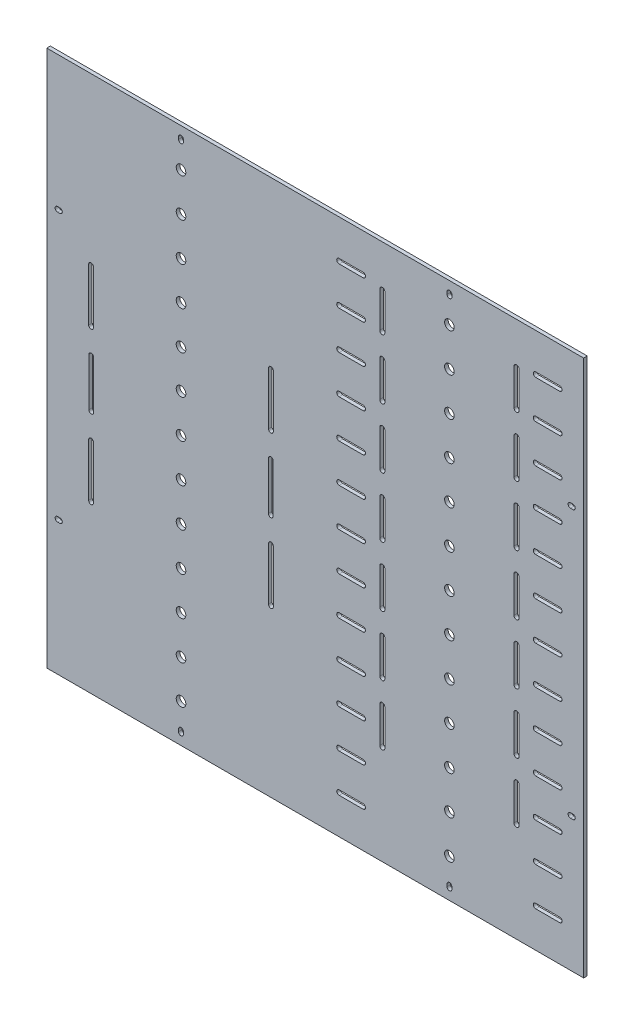
SolidWorks part; units mm, degrees
ref_plane "Piano frontale" through (0, 0, 0) normal (0, 0, 1) x (1, 0, 0)
ref_plane "Piano superiore" through (0, 0, 0) normal (0, 1, 0) x (1, 0, 0)
ref_plane "Piano destro" through (0, 0, 0) normal (1, 0, 0) x (0, 0, -1)
sketch "Schizzo1" plane through (0, 0, 0) normal (0, 0, 1) x (1, 0, 0)
  line L0 (10, 448) -> (10, -28.2593) construction
  line L1 (0, 0) -> (448, 0)
  line L2 (0, 0) -> (0, 448)
  line L3 (0, 448) -> (448, 448)
  line L4 (448, 0) -> (448, 448)
  line L5 (0, 224) -> (448, 224) construction
  line L6 (224, 448) -> (224, 0) construction
  line L7 (438, 448) -> (438, -28.2593) construction
  line L8 (0, 438) -> (525.0128, 438) construction
  line L9 (0, 10) -> (525.0128, 10) construction
  line L10 (0, 448) -> (0, 224) construction
  line L11 (0, 448) -> (0, 224) construction
  line L12 (9, 336) -> (11, 336) construction
  line L13 (9, 338) -> (11, 338)
  line L14 (9, 334) -> (11, 334)
  line L15 (0, 336) -> (224, 336) construction
  line L16 (9, 112) -> (11, 112) construction
  line L17 (9, 110) -> (11, 110)
  line L18 (9, 114) -> (11, 114)
  line L19 (439, 112) -> (437, 112) construction
  line L20 (439, 110) -> (437, 110)
  line L21 (439, 114) -> (437, 114)
  line L22 (439, 336) -> (437, 336) construction
  line L23 (439, 338) -> (437, 338)
  line L24 (439, 334) -> (437, 334)
  line L25 (112, 448) -> (112, 224) construction
  line L26 (112, 439) -> (112, 437) construction
  line L27 (114, 439) -> (114, 437)
  line L28 (110, 439) -> (110, 437)
  line L29 (336, 439) -> (336, 437) construction
  line L30 (334, 439) -> (334, 437)
  line L31 (338, 439) -> (338, 437)
  line L32 (112, 9) -> (112, 11) construction
  line L33 (114, 9) -> (114, 11)
  line L34 (110, 9) -> (110, 11)
  line L35 (336, 9) -> (336, 11) construction
  line L36 (334, 9) -> (334, 11)
  line L37 (338, 9) -> (338, 11)
  line L38 (36.9588, 287.1268) -> (36.9588, 448) construction
  line L39 (36.9588, 265.3661) -> (36.9588, 309.3661) construction
  line L40 (34.9588, 265.3661) -> (34.9588, 309.3661)
  line L41 (38.9588, 265.3661) -> (38.9588, 309.3661)
  line L42 (36.9588, 182.6339) -> (36.9588, 138.6339) construction
  line L43 (34.9588, 182.6339) -> (34.9588, 138.6339)
  line L44 (38.9588, 182.6339) -> (38.9588, 138.6339)
  line L45 (37.087, 204.1388) -> (37.087, 244.1388) construction
  line L46 (35.087, 204.1388) -> (35.087, 244.1388)
  line L47 (39.087, 204.1388) -> (39.087, 244.1388)
  line L48 (187.0412, 265.3661) -> (187.0412, 309.3661) construction
  line L49 (189.0412, 265.3661) -> (189.0412, 309.3661)
  line L50 (185.0412, 265.3661) -> (185.0412, 309.3661)
  line L51 (186.913, 204.1388) -> (186.913, 244.1388) construction
  line L52 (188.913, 204.1388) -> (188.913, 244.1388)
  line L53 (184.913, 204.1388) -> (184.913, 244.1388)
  line L54 (187.0412, 182.6339) -> (187.0412, 138.6339) construction
  line L55 (189.0412, 182.6339) -> (189.0412, 138.6339)
  line L56 (185.0412, 182.6339) -> (185.0412, 138.6339)
  line L57 (243.9707, 416) -> (263.9707, 416) construction
  line L58 (243.9707, 418) -> (263.9707, 418)
  line L59 (243.9707, 414) -> (263.9707, 414)
  line L63 (224, 224) -> (448, 0) construction
  line L64 (448, 224) -> (224, 0) construction
  line L65 (224, 224) -> (448, 224) construction
  line L66 (336, 112) -> (335.9892, 224.0001) construction
  line L67 (336, 112) -> (448, 112) construction
  line L83 (427.9707, 416.0177) -> (407.9707, 416.0139) construction
  line L84 (427.9703, 418.0177) -> (407.9703, 418.0139)
  line L85 (427.9711, 414.0177) -> (407.9711, 414.0139)
  line L89 (243.9707, 384) -> (263.9707, 384) construction
  line L90 (243.9707, 386) -> (263.9707, 386)
  line L91 (243.9707, 382) -> (263.9707, 382)
  line L92 (427.9707, 384.0177) -> (407.9707, 384.0139) construction
  line L93 (427.9703, 386.0177) -> (407.9703, 386.0139)
  line L94 (427.9711, 382.0177) -> (407.9711, 382.0139)
  line L95 (279.9725, 383.005) -> (279.9725, 412.995) construction
  line L96 (277.8725, 383.005) -> (277.8725, 412.995)
  line L97 (282.0725, 383.005) -> (282.0725, 412.995)
  line L98 (243.9707, 352) -> (263.9707, 352) construction
  line L99 (243.9707, 354) -> (263.9707, 354)
  line L100 (243.9707, 350) -> (263.9707, 350)
  line L101 (427.9707, 352.0177) -> (407.9707, 352.0139) construction
  line L102 (427.9703, 354.0177) -> (407.9703, 354.0139)
  line L103 (427.9711, 350.0177) -> (407.9711, 350.0139)
  line L104 (243.9707, 320) -> (263.9707, 320) construction
  line L105 (243.9707, 322) -> (263.9707, 322)
  line L106 (243.9707, 318) -> (263.9707, 318)
  line L107 (427.9707, 320.0177) -> (407.9707, 320.0139) construction
  line L108 (427.9703, 322.0177) -> (407.9703, 322.0139)
  line L109 (427.9711, 318.0177) -> (407.9711, 318.0139)
  line L110 (243.9707, 288) -> (263.9707, 288) construction
  line L111 (391.9724, 383.0058) -> (391.9724, 413.0158) construction
  line L112 (394.0724, 383.0058) -> (394.0724, 413.0158)
  line L113 (389.8724, 383.0058) -> (389.8724, 413.0158)
  line L114 (336, 112) -> (202.345, 112) construction
  line L118 (243.9707, 290) -> (263.9707, 290)
  line L122 (243.9707, 286) -> (263.9707, 286)
  line L132 (427.9707, 288.0177) -> (407.9707, 288.0139) construction
  line L133 (427.9703, 290.0177) -> (407.9703, 290.0139)
  line L134 (427.9711, 286.0177) -> (407.9711, 286.0139)
  line L135 (243.9707, 256) -> (263.9707, 256) construction
  line L136 (243.9707, 258) -> (263.9707, 258)
  line L137 (243.9707, 254) -> (263.9707, 254)
  line L138 (427.9707, 256.0177) -> (407.9707, 256.0139) construction
  line L139 (427.9703, 258.0177) -> (407.9703, 258.0139)
  line L140 (427.9711, 254.0177) -> (407.9711, 254.0139)
  line L141 (243.9707, 224) -> (263.9707, 224) construction
  line L142 (243.9707, 226) -> (263.9707, 226)
  line L143 (243.9707, 222) -> (263.9707, 222)
  line L144 (427.9707, 224.0177) -> (407.9707, 224.0139) construction
  line L145 (427.9703, 226.0177) -> (407.9703, 226.0139)
  line L146 (427.9711, 222.0177) -> (407.9711, 222.0139)
  line L147 (243.9707, 192) -> (263.9707, 192) construction
  line L148 (243.9707, 194) -> (263.9707, 194)
  line L149 (243.9707, 190) -> (263.9707, 190)
  line L150 (427.9707, 192.0177) -> (407.9707, 192.0139) construction
  line L151 (427.9703, 194.0177) -> (407.9703, 194.0139)
  line L152 (427.9711, 190.0177) -> (407.9711, 190.0139)
  line L153 (243.9707, 160) -> (263.9707, 160) construction
  line L154 (243.9707, 162) -> (263.9707, 162)
  line L155 (243.9707, 158) -> (263.9707, 158)
  line L156 (427.9707, 160.0177) -> (407.9707, 160.0139) construction
  line L157 (427.9703, 162.0177) -> (407.9703, 162.0139)
  line L158 (427.9711, 158.0177) -> (407.9711, 158.0139)
  line L159 (243.9707, 128) -> (263.9707, 128) construction
  line L160 (243.9707, 130) -> (263.9707, 130)
  line L161 (243.9707, 126) -> (263.9707, 126)
  line L162 (427.9707, 128.0177) -> (407.9707, 128.0139) construction
  line L163 (427.9703, 130.0177) -> (407.9703, 130.0139)
  line L164 (427.9711, 126.0177) -> (407.9711, 126.0139)
  line L165 (279.9725, 333.005) -> (279.9725, 362.995) construction
  line L166 (277.8725, 333.005) -> (277.8725, 362.995)
  line L167 (282.0725, 333.005) -> (282.0725, 362.995)
  line L168 (391.9724, 333.0058) -> (391.9724, 363.0158) construction
  line L169 (394.0724, 333.0058) -> (394.0724, 363.0158)
  line L170 (389.8724, 333.0058) -> (389.8724, 363.0158)
  line L171 (279.9725, 283.005) -> (279.9725, 312.995) construction
  line L172 (277.8725, 283.005) -> (277.8725, 312.995)
  line L173 (282.0725, 283.005) -> (282.0725, 312.995)
  line L174 (391.9724, 283.0058) -> (391.9724, 313.0158) construction
  line L175 (394.0724, 283.0058) -> (394.0724, 313.0158)
  line L176 (389.8724, 283.0058) -> (389.8724, 313.0158)
  line L177 (279.9725, 233.005) -> (279.9725, 262.995) construction
  line L178 (277.8725, 233.005) -> (277.8725, 262.995)
  line L179 (282.0725, 233.005) -> (282.0725, 262.995)
  line L180 (391.9724, 233.0058) -> (391.9724, 263.0158) construction
  line L181 (394.0724, 233.0058) -> (394.0724, 263.0158)
  line L182 (389.8724, 233.0058) -> (389.8724, 263.0158)
  line L183 (279.9725, 183.005) -> (279.9725, 212.995) construction
  line L184 (277.8725, 183.005) -> (277.8725, 212.995)
  line L185 (282.0725, 183.005) -> (282.0725, 212.995)
  line L186 (391.9724, 183.0058) -> (391.9724, 213.0158) construction
  line L187 (394.0724, 183.0058) -> (394.0724, 213.0158)
  line L188 (389.8724, 183.0058) -> (389.8724, 213.0158)
  line L189 (279.9725, 133.005) -> (279.9725, 162.995) construction
  line L190 (277.8725, 133.005) -> (277.8725, 162.995)
  line L191 (282.0725, 133.005) -> (282.0725, 162.995)
  line L192 (391.9724, 133.0058) -> (391.9724, 163.0158) construction
  line L193 (394.0724, 133.0058) -> (394.0724, 163.0158)
  line L194 (389.8724, 133.0058) -> (389.8724, 163.0158)
  line L195 (279.9725, 83.005) -> (279.9725, 112.995) construction
  line L196 (277.8725, 83.005) -> (277.8725, 112.995)
  line L197 (282.0725, 83.005) -> (282.0725, 112.995)
  line L198 (391.9724, 83.0058) -> (391.9724, 113.0158) construction
  line L199 (394.0724, 83.0058) -> (394.0724, 113.0158)
  line L200 (389.8724, 83.0058) -> (389.8724, 113.0158)
  line L201 (243.9707, 96) -> (263.9707, 96) construction
  line L202 (243.9707, 98) -> (263.9707, 98)
  line L203 (243.9707, 94) -> (263.9707, 94)
  line L204 (427.9707, 96.0177) -> (407.9707, 96.0139) construction
  line L205 (427.9703, 98.0177) -> (407.9703, 98.0139)
  line L206 (427.9711, 94.0177) -> (407.9711, 94.0139)
  line L207 (243.9707, 64) -> (263.9707, 64) construction
  line L208 (243.9707, 66) -> (263.9707, 66)
  line L209 (243.9707, 62) -> (263.9707, 62)
  line L210 (427.9707, 64.0177) -> (407.9707, 64.0139) construction
  line L211 (427.9703, 66.0177) -> (407.9703, 66.0139)
  line L212 (427.9711, 62.0177) -> (407.9711, 62.0139)
  line L213 (243.9707, 32) -> (263.9707, 32) construction
  line L214 (243.9707, 34) -> (263.9707, 34)
  line L215 (243.9707, 30) -> (263.9707, 30)
  line L216 (427.9707, 32.0177) -> (407.9707, 32.0139) construction
  line L217 (427.9703, 34.0177) -> (407.9703, 34.0139)
  line L218 (427.9711, 30.0177) -> (407.9711, 30.0139)
  arc A0 (9, 338) -> (9, 334) centre (9, 336) ccw
  arc A1 (11, 334) -> (11, 338) centre (11, 336) ccw
  arc A2 (9, 110) -> (9, 114) centre (9, 112) cw
  arc A3 (11, 114) -> (11, 110) centre (11, 112) cw
  arc A4 (439, 110) -> (439, 114) centre (439, 112) ccw
  arc A5 (437, 114) -> (437, 110) centre (437, 112) ccw
  arc A6 (439, 338) -> (439, 334) centre (439, 336) cw
  arc A7 (437, 334) -> (437, 338) centre (437, 336) cw
  arc A8 (114, 439) -> (110, 439) centre (112, 439) ccw
  arc A9 (110, 437) -> (114, 437) centre (112, 437) ccw
  arc A10 (334, 439) -> (338, 439) centre (336, 439) cw
  arc A11 (338, 437) -> (334, 437) centre (336, 437) cw
  arc A12 (114, 9) -> (110, 9) centre (112, 9) cw
  arc A13 (110, 11) -> (114, 11) centre (112, 11) cw
  arc A14 (334, 9) -> (338, 9) centre (336, 9) ccw
  arc A15 (338, 11) -> (334, 11) centre (336, 11) ccw
  arc A16 (34.9588, 265.3661) -> (38.9588, 265.3661) centre (36.9588, 265.3661) ccw
  arc A17 (38.9588, 309.3661) -> (34.9588, 309.3661) centre (36.9588, 309.3661) ccw
  arc A18 (34.9588, 182.6339) -> (38.9588, 182.6339) centre (36.9588, 182.6339) cw
  arc A19 (38.9588, 138.6339) -> (34.9588, 138.6339) centre (36.9588, 138.6339) cw
  arc A20 (35.087, 204.1388) -> (39.087, 204.1388) centre (37.087, 204.1388) ccw
  arc A21 (39.087, 244.1388) -> (35.087, 244.1388) centre (37.087, 244.1388) ccw
  arc A22 (189.0412, 265.3661) -> (185.0412, 265.3661) centre (187.0412, 265.3661) cw
  arc A23 (185.0412, 309.3661) -> (189.0412, 309.3661) centre (187.0412, 309.3661) cw
  arc A24 (188.913, 204.1388) -> (184.913, 204.1388) centre (186.913, 204.1388) cw
  arc A25 (184.913, 244.1388) -> (188.913, 244.1388) centre (186.913, 244.1388) cw
  arc A26 (189.0412, 182.6339) -> (185.0412, 182.6339) centre (187.0412, 182.6339) ccw
  arc A27 (185.0412, 138.6339) -> (189.0412, 138.6339) centre (187.0412, 138.6339) ccw
  arc A28 (243.9707, 418) -> (243.9707, 414) centre (243.9707, 416) ccw
  arc A29 (263.9707, 414) -> (263.9707, 418) centre (263.9707, 416) ccw
  arc A36 (427.9703, 418.0177) -> (427.9711, 414.0177) centre (427.9707, 416.0177) cw
  arc A37 (407.9711, 414.0139) -> (407.9703, 418.0139) centre (407.9707, 416.0139) cw
  arc A38 (243.9707, 386) -> (243.9707, 382) centre (243.9707, 384) ccw
  arc A39 (263.9707, 382) -> (263.9707, 386) centre (263.9707, 384) ccw
  arc A40 (427.9703, 386.0177) -> (427.9711, 382.0177) centre (427.9707, 384.0177) cw
  arc A41 (407.9711, 382.0139) -> (407.9703, 386.0139) centre (407.9707, 384.0139) cw
  arc A42 (243.9707, 354) -> (243.9707, 350) centre (243.9707, 352) ccw
  arc A43 (263.9707, 350) -> (263.9707, 354) centre (263.9707, 352) ccw
  arc A44 (427.9703, 354.0177) -> (427.9711, 350.0177) centre (427.9707, 352.0177) cw
  arc A45 (407.9711, 350.0139) -> (407.9703, 354.0139) centre (407.9707, 352.0139) cw
  circle A48 centre (335.9707, 416) radius 4
  circle A49 centre (335.9707, 384) radius 4
  arc A52 (243.9707, 322) -> (243.9707, 318) centre (243.9707, 320) ccw
  arc A53 (263.9707, 318) -> (263.9707, 322) centre (263.9707, 320) ccw
  arc A56 (427.9703, 322.0177) -> (427.9711, 318.0177) centre (427.9707, 320.0177) cw
  arc A57 (407.9711, 318.0139) -> (407.9703, 322.0139) centre (407.9707, 320.0139) cw
  arc A58 (243.9707, 290) -> (243.9707, 286) centre (243.9707, 288) ccw
  arc A59 (263.9707, 286) -> (263.9707, 290) centre (263.9707, 288) ccw
  arc A60 (277.8725, 383.005) -> (282.0725, 383.005) centre (279.9725, 383.005) ccw
  arc A61 (282.0725, 412.995) -> (277.8725, 412.995) centre (279.9725, 412.995) ccw
  arc A62 (427.9703, 290.0177) -> (427.9711, 286.0177) centre (427.9707, 288.0177) cw
  arc A63 (407.9711, 286.0139) -> (407.9703, 290.0139) centre (407.9707, 288.0139) cw
  arc A64 (243.9707, 258) -> (243.9707, 254) centre (243.9707, 256) ccw
  arc A65 (263.9707, 254) -> (263.9707, 258) centre (263.9707, 256) ccw
  arc A66 (427.9703, 258.0177) -> (427.9711, 254.0177) centre (427.9707, 256.0177) cw
  arc A67 (407.9711, 254.0139) -> (407.9703, 258.0139) centre (407.9707, 256.0139) cw
  arc A68 (243.9707, 226) -> (243.9707, 222) centre (243.9707, 224) ccw
  arc A69 (263.9707, 222) -> (263.9707, 226) centre (263.9707, 224) ccw
  arc A70 (394.0724, 383.0058) -> (389.8724, 383.0058) centre (391.9724, 383.0058) cw
  arc A71 (389.8724, 413.0158) -> (394.0724, 413.0158) centre (391.9724, 413.0158) cw
  arc A82 (427.9703, 226.0177) -> (427.9711, 222.0177) centre (427.9707, 224.0177) cw
  arc A83 (407.9711, 222.0139) -> (407.9703, 226.0139) centre (407.9707, 224.0139) cw
  arc A84 (243.9707, 194) -> (243.9707, 190) centre (243.9707, 192) ccw
  arc A85 (263.9707, 190) -> (263.9707, 194) centre (263.9707, 192) ccw
  arc A86 (427.9703, 194.0177) -> (427.9711, 190.0177) centre (427.9707, 192.0177) cw
  arc A87 (407.9711, 190.0139) -> (407.9703, 194.0139) centre (407.9707, 192.0139) cw
  arc A88 (243.9707, 162) -> (243.9707, 158) centre (243.9707, 160) ccw
  arc A89 (263.9707, 158) -> (263.9707, 162) centre (263.9707, 160) ccw
  arc A90 (427.9703, 162.0177) -> (427.9711, 158.0177) centre (427.9707, 160.0177) cw
  arc A91 (407.9711, 158.0139) -> (407.9703, 162.0139) centre (407.9707, 160.0139) cw
  arc A92 (243.9707, 130) -> (243.9707, 126) centre (243.9707, 128) ccw
  arc A93 (263.9707, 126) -> (263.9707, 130) centre (263.9707, 128) ccw
  arc A94 (427.9703, 130.0177) -> (427.9711, 126.0177) centre (427.9707, 128.0177) cw
  arc A95 (407.9711, 126.0139) -> (407.9703, 130.0139) centre (407.9707, 128.0139) cw
  arc A96 (277.8725, 333.005) -> (282.0725, 333.005) centre (279.9725, 333.005) ccw
  arc A97 (282.0725, 362.995) -> (277.8725, 362.995) centre (279.9725, 362.995) ccw
  arc A98 (394.0724, 333.0058) -> (389.8724, 333.0058) centre (391.9724, 333.0058) cw
  arc A99 (389.8724, 363.0158) -> (394.0724, 363.0158) centre (391.9724, 363.0158) cw
  arc A100 (277.8725, 283.005) -> (282.0725, 283.005) centre (279.9725, 283.005) ccw
  arc A101 (282.0725, 312.995) -> (277.8725, 312.995) centre (279.9725, 312.995) ccw
  arc A102 (394.0724, 283.0058) -> (389.8724, 283.0058) centre (391.9724, 283.0058) cw
  arc A103 (389.8724, 313.0158) -> (394.0724, 313.0158) centre (391.9724, 313.0158) cw
  arc A104 (277.8725, 233.005) -> (282.0725, 233.005) centre (279.9725, 233.005) ccw
  arc A105 (282.0725, 262.995) -> (277.8725, 262.995) centre (279.9725, 262.995) ccw
  arc A106 (394.0724, 233.0058) -> (389.8724, 233.0058) centre (391.9724, 233.0058) cw
  arc A107 (389.8724, 263.0158) -> (394.0724, 263.0158) centre (391.9724, 263.0158) cw
  arc A108 (277.8725, 183.005) -> (282.0725, 183.005) centre (279.9725, 183.005) ccw
  arc A109 (282.0725, 212.995) -> (277.8725, 212.995) centre (279.9725, 212.995) ccw
  arc A110 (394.0724, 183.0058) -> (389.8724, 183.0058) centre (391.9724, 183.0058) cw
  arc A111 (389.8724, 213.0158) -> (394.0724, 213.0158) centre (391.9724, 213.0158) cw
  arc A112 (277.8725, 133.005) -> (282.0725, 133.005) centre (279.9725, 133.005) ccw
  arc A113 (282.0725, 162.995) -> (277.8725, 162.995) centre (279.9725, 162.995) ccw
  arc A114 (394.0724, 133.0058) -> (389.8724, 133.0058) centre (391.9724, 133.0058) cw
  arc A115 (389.8724, 163.0158) -> (394.0724, 163.0158) centre (391.9724, 163.0158) cw
  arc A116 (277.8725, 83.005) -> (282.0725, 83.005) centre (279.9725, 83.005) ccw
  arc A117 (282.0725, 112.995) -> (277.8725, 112.995) centre (279.9725, 112.995) ccw
  arc A118 (394.0724, 83.0058) -> (389.8724, 83.0058) centre (391.9724, 83.0058) cw
  arc A119 (389.8724, 113.0158) -> (394.0724, 113.0158) centre (391.9724, 113.0158) cw
  arc A120 (243.9707, 98) -> (243.9707, 94) centre (243.9707, 96) ccw
  arc A121 (263.9707, 94) -> (263.9707, 98) centre (263.9707, 96) ccw
  arc A122 (427.9703, 98.0177) -> (427.9711, 94.0177) centre (427.9707, 96.0177) cw
  arc A123 (407.9711, 94.0139) -> (407.9703, 98.0139) centre (407.9707, 96.0139) cw
  arc A124 (243.9707, 66) -> (243.9707, 62) centre (243.9707, 64) ccw
  arc A125 (263.9707, 62) -> (263.9707, 66) centre (263.9707, 64) ccw
  arc A126 (427.9703, 66.0177) -> (427.9711, 62.0177) centre (427.9707, 64.0177) cw
  arc A127 (407.9711, 62.0139) -> (407.9703, 66.0139) centre (407.9707, 64.0139) cw
  arc A128 (243.9707, 34) -> (243.9707, 30) centre (243.9707, 32) ccw
  arc A129 (263.9707, 30) -> (263.9707, 34) centre (263.9707, 32) ccw
  arc A130 (427.9703, 34.0177) -> (427.9711, 30.0177) centre (427.9707, 32.0177) cw
  arc A131 (407.9711, 30.0139) -> (407.9703, 34.0139) centre (407.9707, 32.0139) cw
  circle A132 centre (335.9707, 352) radius 4
  circle A133 centre (335.9707, 320) radius 4
  circle A134 centre (335.9707, 288) radius 4
  circle A135 centre (335.9707, 256) radius 4
  circle A136 centre (335.9707, 224) radius 4
  circle A137 centre (335.9707, 192) radius 4
  circle A138 centre (335.9707, 160) radius 4
  circle A139 centre (335.9707, 128) radius 4
  circle A140 centre (335.9707, 96) radius 4
  circle A141 centre (335.9707, 64) radius 4
  circle A142 centre (335.9707, 32) radius 4
  circle A143 centre (112.0293, 32) radius 4
  circle A144 centre (112.0293, 64) radius 4
  circle A145 centre (112.0293, 96) radius 4
  circle A146 centre (112.0293, 128) radius 4
  circle A147 centre (112.0293, 160) radius 4
  circle A148 centre (112.0293, 192) radius 4
  circle A149 centre (112.0293, 224) radius 4
  circle A150 centre (112.0293, 256) radius 4
  circle A151 centre (112.0293, 288) radius 4
  circle A152 centre (112.0293, 320) radius 4
  circle A153 centre (112.0293, 352) radius 4
  circle A154 centre (112.0293, 384) radius 4
  circle A155 centre (112.0293, 416) radius 4
  point P19 (10, 336)
  point P28 (10, 112)
  point P35 (438, 112)
  point P42 (438, 336)
  point P49 (112, 438)
  point P52 (112, 438)
  point P59 (336, 438)
  point P66 (112, 10)
  point P73 (336, 10)
  point P82 (36.9588, 287.3661)
  point P89 (36.9588, 160.6339)
  point P96 (37.087, 224.1388)
  point P103 (187.0412, 287.3661)
  point P110 (186.913, 224.1388)
  point P117 (187.0412, 160.6339)
  point P124 (253.9707, 416)
  point P155 (417.9707, 416.0158)
  point P164 (253.9707, 384)
  point P171 (417.9707, 384.0158)
  point P179 (280.1758, 232.4048)
  point P193 (280.1085, 282.4047)
  point P197 (253.9707, 352)
  point P207 (280.0413, 332.4047)
  point P214 (417.9707, 352.0158)
  point P221 (253.9707, 320)
  point P227 (279.9725, 398)
  point P235 (417.9707, 320.0158)
  point P242 (253.9707, 288)
  point P249 (417.9707, 288.0158)
  point P256 (253.9707, 256)
  point P262 (391.9724, 398.0108)
  point P307 (417.9707, 256.0158)
  point P314 (253.9707, 224)
  point P321 (417.9707, 224.0158)
  point P328 (253.9707, 192)
  point P335 (417.9707, 192.0158)
  point P342 (253.9707, 160)
  point P349 (417.9707, 160.0158)
  point P356 (253.9707, 128)
  point P363 (417.9707, 128.0158)
  point P370 (279.9725, 348)
  point P377 (391.9724, 348.0108)
  point P384 (279.9725, 298)
  point P391 (391.9724, 298.0108)
  point P398 (279.9725, 248)
  point P405 (391.9724, 248.0108)
  point P412 (279.9725, 198)
  point P419 (391.9724, 198.0108)
  point P426 (279.9725, 148)
  point P433 (391.9724, 148.0108)
  point P440 (279.9725, 98)
  point P447 (391.9724, 98.0108)
  point P454 (253.9707, 96)
  point P461 (417.9707, 96.0158)
  point P468 (253.9707, 64)
  point P475 (417.9707, 64.0158)
  point P482 (253.9707, 32)
  point P489 (417.9707, 32.0158)
  dimension "D5" = 1
  dimension "D14" = 82
  dimension "D21" = 7
  dimension "D18" = 8
  dimension "D1" = 448
  dimension "D2" = 448
  dimension "D3" = 10
  dimension "D4" = 10
  dimension "D6" = 4
  dimension "D7" = 112
  dimension "D8" = 112
  dimension "D9" = 1
  dimension "D10" = 4
  dimension "D11" = 4
  dimension "D12" = 22
  dimension "D13" = 4
  dimension "D15" = 32
  dimension "D16" = 20
  dimension "D17" = 50
  dimension "D20" = 13
  dimension "D25" = 112
extrude "Estrusione-Estrusione1" add sketch "Schizzo1" against normal blind 3
